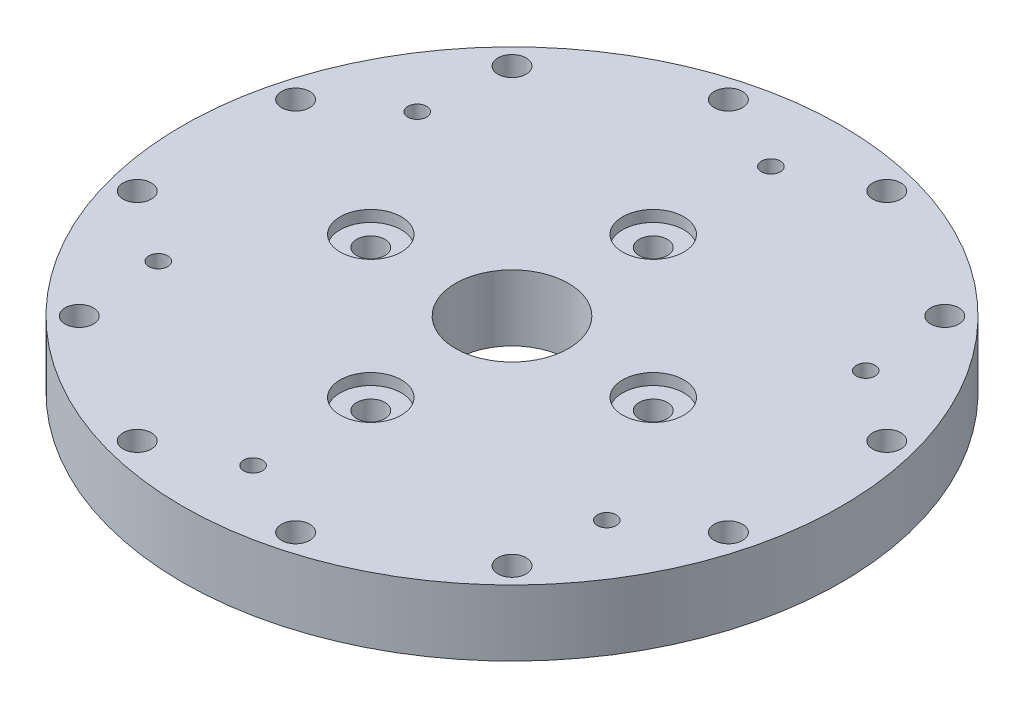
SolidWorks part; units mm, degrees
ref_plane "Front Plane" through (0, 0, 0) normal (0, 0, 1) x (1, 0, 0)
ref_plane "Top Plane" through (0, 0, 0) normal (0, 1, 0) x (1, 0, 0)
ref_plane "Right Plane" through (0, 0, 0) normal (1, 0, 0) x (0, 0, -1)
sketch "Sketch1" plane through (0, 0, 0) normal (0, 1, 0) x (1, 0, 0)
  line L0 (-49.4318, 0) -> (0, 0) construction
  line L1 (0, 0) -> (-47.2333, -12.6561) construction
  circle A0 centre (0, 0) radius 35
  circle A1 centre (0, 0) radius 27.5 construction
  circle A2 centre (0, 0) radius 6
  circle A3 centre (0, 0) radius 15 construction
  circle A4 centre (0, 15) radius 1.5
  circle A5 centre (15, 0) radius 1.5
  circle A6 centre (0, -15) radius 1.5
  circle A7 centre (-15, 0) radius 1.5
  circle A11 centre (0, 0) radius 32.5 construction
  circle A12 centre (-31.3926, -8.4116) radius 1.5
  circle A13 centre (-31.3926, 8.4116) radius 1.5
  circle A14 centre (-22.981, 22.981) radius 1.5
  circle A15 centre (-8.4116, 31.3926) radius 1.5
  circle A16 centre (8.4116, 31.3926) radius 1.5
  circle A17 centre (22.981, 22.981) radius 1.5
  circle A18 centre (31.3926, 8.4116) radius 1.5
  circle A19 centre (31.3926, -8.4116) radius 1.5
  circle A20 centre (22.981, -22.981) radius 1.5
  circle A21 centre (8.4116, -31.3926) radius 1.5
  circle A22 centre (-8.4116, -31.3926) radius 1.5
  circle A23 centre (-22.981, -22.981) radius 1.5
  circle A24 centre (0, 27.5) radius 1
  circle A25 centre (23.8157, 13.75) radius 1
  circle A26 centre (23.8157, -13.75) radius 1
  circle A27 centre (0, -27.5) radius 1
  circle A28 centre (-23.8157, -13.75) radius 1
  circle A29 centre (-23.8157, 13.75) radius 1
  point P17 (0, 0)
  point P44 (0, 0)
  point P57 (0, 0)
  dimension "D1" = 70
  dimension "D2" = 55
  dimension "D3" = 12
  dimension "D4" = 3
  dimension "D6" = 30
  dimension "D7" = 65
  dimension "D9" = 3
  dimension "D11" = 2
  dimension "D8" = 15
  dimension "D5" = 4
  dimension "D10" = 12
  dimension "D12" = 6
extrude "Boss-Extrude1" add sketch "Sketch1" along normal blind 7
sketch "Sketch2" plane through (0, 7, 0) normal (0, 1, 0) x (1, 0, 0)
  circle A0 centre (0, 0) radius 15 construction
  circle A1 centre (0, 15) radius 3.25
  circle A2 centre (15, 0) radius 3.25
  circle A3 centre (0, -15) radius 3.25
  circle A4 centre (-15, 0) radius 3.25
  point P15 (0, 0)
  dimension "D1" = 6.5
  dimension "D2" = 4
extrude "Cut-Extrude1" cut sketch "Sketch2" against normal blind 1.2
